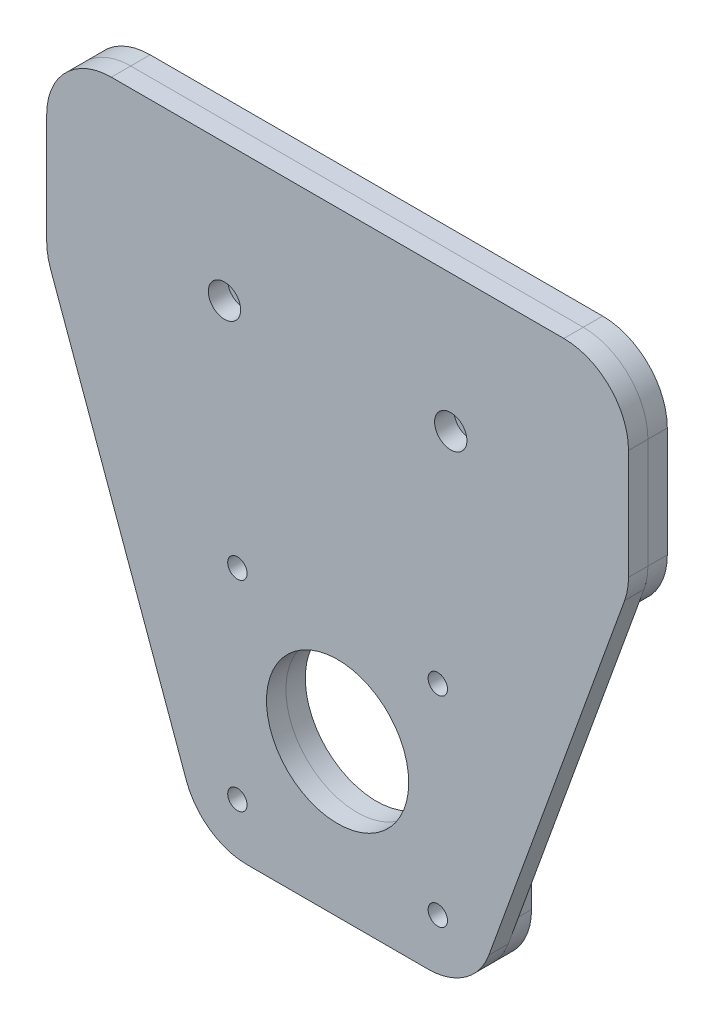
SolidWorks part; units mm, degrees
ref_plane "Alzado" through (0, 0, 0) normal (0, 0, 1) x (1, 0, 0)
ref_plane "Planta" through (0, 0, 0) normal (0, 1, 0) x (1, 0, 0)
ref_plane "Vista lateral" through (0, 0, 0) normal (1, 0, 0) x (0, 0, -1)
sketch "Croquis1" plane through (0, 0, 0) normal (0, 0, 1) x (1, 0, 0)
  line L0 (0, 10) -> (0, 58)
  line L1 (0, 58) -> (-11, 58)
  line L2 (-21, 68) -> (-21, 85)
  line L3 (-11, 95) -> (59, 95)
  line L4 (69, 85) -> (69, 68)
  line L5 (59, 58) -> (48, 58)
  line L6 (48, 58) -> (48, 10)
  line L7 (38, 0) -> (10, 0)
  line L8 (8.5, 39) -> (8.5, 8) construction
  line L9 (24, 95) -> (24, 0) construction
  line L10 (8.5, 39) -> (39.5, 8) construction
  line L11 (39.5, 39) -> (8.5, 8) construction
  circle A0 centre (8.5, 39) radius 1.5
  circle A1 centre (39.5, 39) radius 1.5
  circle A2 centre (39.5, 8) radius 1.5
  circle A3 centre (8.5, 8) radius 1.5
  circle A4 centre (6.5, 76.5) radius 2.5
  circle A5 centre (41.5, 76.5) radius 2.5
  circle A6 centre (24, 23.5) radius 11
  arc A7 (0, 10) -> (10, 0) centre (10, 10) ccw
  arc A8 (48, 10) -> (38, 0) centre (38, 10) cw
  arc A9 (69, 68) -> (59, 58) centre (59, 68) cw
  arc A10 (59, 95) -> (69, 85) centre (59, 85) cw
  arc A11 (-11, 58) -> (-21, 68) centre (-11, 68) cw
  arc A12 (-21, 85) -> (-11, 95) centre (-11, 85) cw
  point P9 (24, 0)
  point P10 (24, 95)
  point P30 (0, 0)
  point P33 (48, 0)
  point P36 (69, 58)
  point P39 (69, 95)
  point P44 (-21, 95)
  dimension "D5" = 3
  dimension "D6" = 8.5
  dimension "D10" = 5
  dimension "D11" = 17.5
  dimension "D12" = 37.5
  dimension "D13" = 18.5
  dimension "D14" = 8.5
  dimension "D15" = 8.5
  dimension "D16" = 22
  dimension "D17" = 10
  dimension "D1" = 90
  dimension "D2" = 37
  dimension "D3" = 95
  dimension "D4" = 48
  dimension "D9" = 31
  dimension "D7" = 2
  dimension "D8" = 2
extrude "Saliente-Extruir1" add sketch "Croquis1" along normal blind 3
sketch "Croquis2" plane through (0, 0, 3) normal (0, 0, 1) x (1, 0, 0)
  line L0 (-20.4027, 64.5956) -> (0.5973, 6.5956)
  line L1 (68.4027, 64.5956) -> (47.4027, 6.5956)
  line L8 (-11, 58) -> (0, 58)
  line L9 (0, 58) -> (0, 10)
  line L10 (10, 0) -> (38, 0)
  line L11 (48, 10) -> (48, 58)
  line L12 (48, 58) -> (59, 58)
  line L13 (69, 68) -> (69, 85)
  line L14 (59, 95) -> (-11, 95)
  line L15 (-21, 85) -> (-21, 68)
  line L18 (10, 0) -> (38, 0)
  line L21 (69, 68) -> (69, 85)
  line L22 (59, 95) -> (-11, 95)
  line L23 (-21, 85) -> (-21, 68)
  arc A0 (-21, 68) -> (-11, 58) centre (-11, 68) ccw construction
  arc A1 (0, 10) -> (10, 0) centre (10, 10) ccw construction
  arc A2 (38, 0) -> (48, 10) centre (38, 10) ccw construction
  arc A3 (59, 58) -> (69, 68) centre (59, 68) ccw construction
  circle A4 centre (6.5, 76.5) radius 2.5
  circle A5 centre (41.5, 76.5) radius 2.5
  arc A6 (0, 10) -> (10, 0) centre (10, 10) ccw
  arc A7 (38, 0) -> (48, 10) centre (38, 10) ccw
  arc A8 (59, 58) -> (69, 68) centre (59, 68) ccw
  arc A9 (69, 85) -> (59, 95) centre (59, 85) ccw
  arc A10 (-11, 95) -> (-21, 85) centre (-11, 85) ccw
  arc A11 (-21, 68) -> (-11, 58) centre (-11, 68) ccw
  arc A12 (0.5973, 6.5956) -> (10, 0) centre (10, 10) ccw
  arc A13 (38, 0) -> (47.4027, 6.5956) centre (38, 10) ccw
  arc A14 (68.4027, 64.5956) -> (69, 68) centre (59, 68) ccw
  arc A15 (69, 85) -> (59, 95) centre (59, 85) ccw
  arc A16 (-11, 95) -> (-21, 85) centre (-11, 85) ccw
  arc A17 (-21, 68) -> (-20.4027, 64.5956) centre (-11, 68) ccw
  circle A18 centre (39.5, 39) radius 1.5
  circle A19 centre (8.5, 39) radius 1.5
  circle A20 centre (8.5, 8) radius 1.5
  circle A21 centre (39.5, 8) radius 1.5
  circle A22 centre (24, 23.5) radius 11
  circle A23 centre (6.5, 73.82) radius 2.5
  circle A24 centre (41.5, 73.82) radius 2.5
  line M17 (-11, 58) -> (0, 58)
  line M18 (0, 58) -> (0, 10)
  arc M19 (0, 10) -> (10, 0) centre (10, 10) ccw
  line M20 (10, 0) -> (38, 0)
  arc M21 (38, 0) -> (48, 10) centre (38, 10) ccw
  line M22 (48, 10) -> (48, 58)
  line M23 (48, 58) -> (59, 58)
  arc M24 (59, 58) -> (69, 68) centre (59, 68) ccw
  line M25 (69, 68) -> (69, 85)
  arc M26 (69, 85) -> (59, 95) centre (59, 85) ccw
  line M27 (59, 95) -> (-11, 95)
  arc M28 (-11, 95) -> (-21, 85) centre (-11, 85) ccw
  line M29 (-21, 85) -> (-21, 68)
  arc M30 (-21, 68) -> (-11, 58) centre (-11, 68) ccw
  circle M31 centre (8.5, 39) radius 1.5
  circle M33 centre (39.5, 39) radius 1.5
  circle M34 centre (39.5, 8) radius 1.5
  circle M35 centre (8.5, 8) radius 1.5
  circle M37 centre (24, 23.5) radius 11
  dimension "D2" = 5
  dimension "D3" = 5
  dimension "D4" = 3
  dimension "D5" = 3
  dimension "D6" = 22
  dimension "D7" = 3
  dimension "D8" = 3
  dimension "D9" = 2.68
  dimension "D10" = 2.68
  dimension "D1" = 0
extrude "Saliente-Extruir2" add sketch "Croquis2" along normal blind 3 separate body contours A24 A5 A23 A4 M30 M17 M18 M19 M20 M21 M22 M23 M24 M25 M26 M27 M28 M29 M31 M33 M35 M37 M34 | L1 M24 M23 M22 M21 | L0 M30 M19 M18 M17 | A23 A4 | A24 A5
